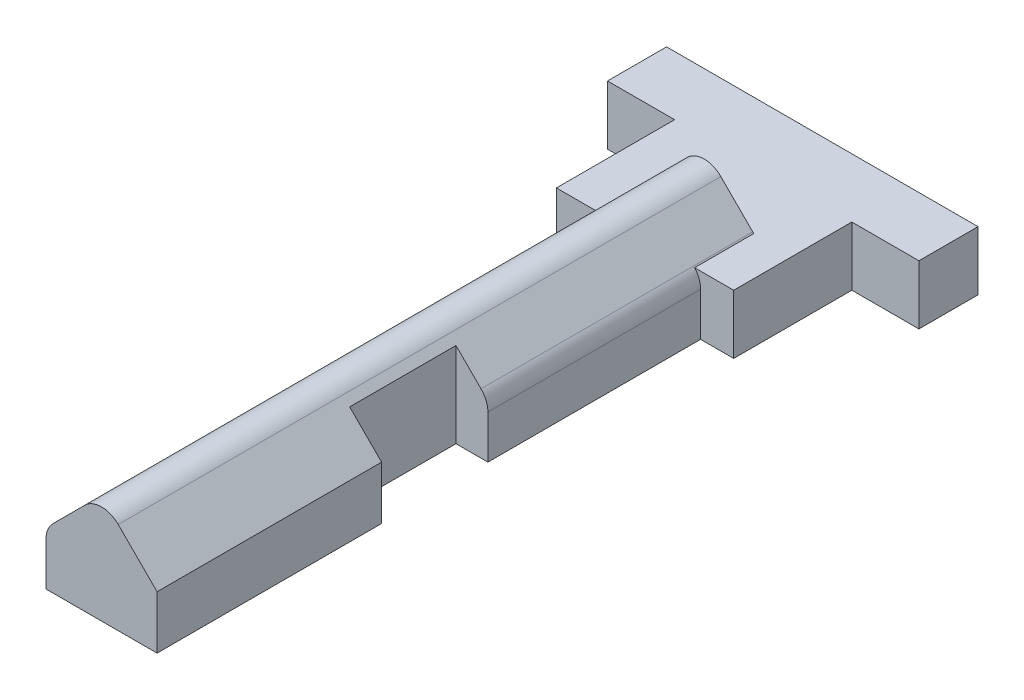
SolidWorks part; units mm, degrees
ref_plane "Płaszczyzna przednia" through (0, 0, 0) normal (0, 0, 1) x (1, 0, 0)
ref_plane "Płaszczyzna górna" through (0, 0, 0) normal (0, 1, 0) x (1, 0, 0)
ref_plane "Płaszczyzna prawa" through (0, 0, 0) normal (1, 0, 0) x (0, 0, -1)
sketch "Szkic1" plane through (0, 0, 0) normal (0, 0, 1) x (1, 0, 0)
  line L0 (0, 0) -> (0, 9.4056) construction
  line L1 (-4.7, 2.25) -> (4.7, 2.25)
  line L2 (-4.7, 2.25) -> (-4.7, -2.25)
  line L3 (-4.7, -2.25) -> (4.7, -2.25)
  line L4 (4.7, 2.25) -> (4.7, -2.25)
  line L5 (-4.7, 2.25) -> (4.7, -2.25) construction
  line L6 (-4.7, -2.25) -> (4.7, 2.25) construction
  line L7 (-4.7, 2.25) -> (0, 6.95)
  line L8 (0, 6.95) -> (4.7, 2.25)
  point P0 (0, 0)
  dimension "D1" = 9.4
  dimension "D2" = 4.5
  dimension "D3" = 45
extrude "Dodanie-wyciągnięcie1" add sketch "Szkic1" along normal blind 51 contours L8 L7 L1 | L4 L1 L2 L3
sketch "Szkic2" plane through (0, -2.25, 0) normal (0, -1, 0) x (1, 0, 0)
  line L0 (0, 0) -> (0, 51) construction
  line L1 (-4.7, 0) -> (4.7, 0) construction
  line L2 (-4.7, 51) -> (4.7, 51) construction
  line L3 (2, 32) -> (2, 23)
  line L4 (0, 23) -> (10, 23)
  line L5 (0, 23) -> (0, 32)
  line L6 (0, 32) -> (10, 32)
  line L7 (10, 23) -> (10, 32)
  line M6 (4.7, 0) -> (4.7, 51)
  dimension "D1" = 10
  dimension "D2" = 9
  dimension "D3" = 23
  dimension "D4" = 2
extrude "Wytnij-wyciągnięcie1" cut sketch "Szkic2" against normal blind 10 contours L6 L3 L4 M6 | L4 L7 L6 M6
ref_plane "Płaszczyzna1" through (-22.5, 11.75, 5) normal (0, -1, 0) x (-1, 0, 0)
sketch "Szkic4" plane through (0, -2.25, 0) normal (0, -1, 0) x (1, 0, 0)
  line L0 (0, 0) -> (0, 5) construction
  line L2 (-4.7, 0) -> (4.7, 0) construction
  line L3 (0, 0) -> (0, -7.3747) construction
  line L9 (7.5, -5) -> (-7.5, -5)
  line L10 (7.5, -5) -> (7.5, 5)
  line L11 (7.5, 5) -> (-7.5, 5)
  line L12 (-7.5, -5) -> (-7.5, 5)
  line L13 (7.5, -5) -> (-7.5, 5) construction
  line L14 (7.5, 5) -> (-7.5, -5) construction
  line L15 (13.1781, -10) -> (-13.1781, -10)
  line L16 (13.1781, -10) -> (13.1781, -5)
  line L17 (13.1781, -5) -> (-13.1781, -5)
  line L18 (-13.1781, -10) -> (-13.1781, -5)
  line L19 (13.1781, -10) -> (-13.1781, -5) construction
  line L20 (13.1781, -5) -> (-13.1781, -10) construction
  point P4 (0, 0)
  point P10 (0, -7.5)
  line M14 (-4.7, 51) -> (-4.7, 0)
  line M15 (-4.7, 0) -> (4.7, 0)
  line M16 (4.7, 0) -> (4.7, 23)
  dimension "D1" = 5
  dimension "D2" = 15
  dimension "D3" = 10
  dimension "D4" = 5
extrude "Dodanie-wyciągnięcie2" add sketch "Szkic4" against normal blind 5 contours L18 L15 L16 L17 L9 | L12 L9 L10 L11 M16 M15 M14
fillet "Zaokrąglenie1" radius 2 3 edges at (4.7, 2.25, 14) (-4.7, 2.25, 28) (0, 6.95, 25.5)
